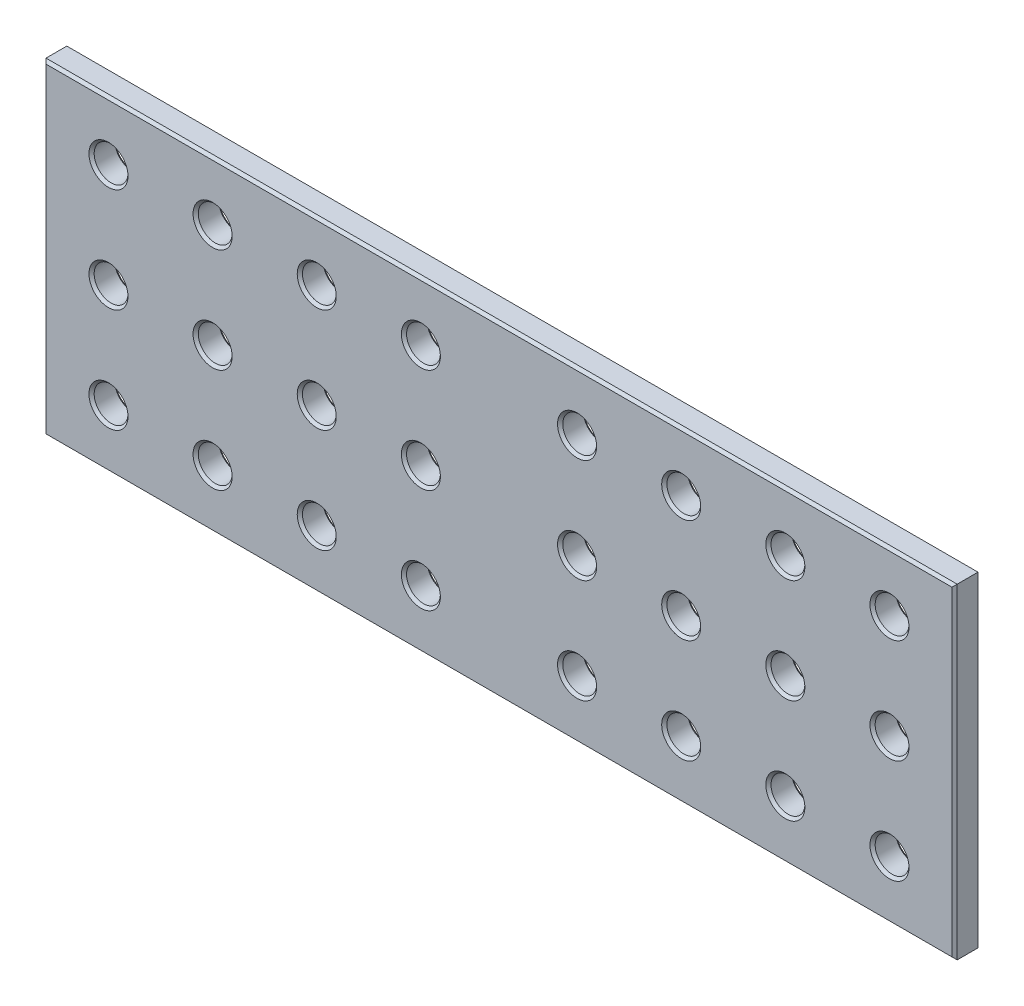
SolidWorks part; units mm, degrees
ref_plane "前视" through (0, 0, 0) normal (0, 0, 1) x (1, 0, 0)
ref_plane "上视" through (0, 0, 0) normal (0, 1, 0) x (1, 0, 0)
ref_plane "右视" through (0, 0, 0) normal (1, 0, 0) x (0, 0, -1)
sketch "草图1" plane through (0, 0, 0) normal (0, 0, 1) x (1, 0, 0)
  line L0 (0, -309.0802) -> (0, 309.0802) construction
  line L1 (-350, -125) -> (350, -125)
  line L2 (-350, -125) -> (-350, 125)
  line L3 (-350, 125) -> (350, 125)
  line L4 (350, -125) -> (350, 125)
  line L5 (-416.575, 0) -> (416.575, 0) construction
  line L6 (-60, 231.9077) -> (-60, -177.8082) construction
  line L7 (-405.3499, 80) -> (106.7949, 80) construction
  line L8 (-300, 281.0174) -> (-300, -177.8082) construction
  line L9 (-140, 189.8136) -> (-140, -190.9976) construction
  line L10 (-220, 297.8551) -> (-220, -190.9976) construction
  circle A0 centre (-300, 80) radius 13
  circle A1 centre (-220, 80) radius 13
  circle A2 centre (-140, 80) radius 13
  circle A3 centre (-60, 80) radius 13
  circle A4 centre (-60, 0) radius 13
  circle A5 centre (-220, 0) radius 13
  circle A6 centre (-300, 0) radius 13
  circle A7 centre (-140, 0) radius 13
  circle A8 centre (-60, -80) radius 13
  circle A9 centre (-140, -80) radius 13
  circle A10 centre (-220, -80) radius 13
  circle A11 centre (-300, -80) radius 13
  circle A12 centre (300, -80) radius 13
  circle A13 centre (220, -80) radius 13
  circle A14 centre (140, -80) radius 13
  circle A15 centre (60, -80) radius 13
  circle A16 centre (140, 0) radius 13
  circle A17 centre (300, 0) radius 13
  circle A18 centre (220, 0) radius 13
  circle A19 centre (60, 0) radius 13
  circle A20 centre (60, 80) radius 13
  circle A21 centre (140, 80) radius 13
  circle A22 centre (220, 80) radius 13
  circle A23 centre (300, 80) radius 13
  dimension "D6" = 26
  dimension "D1" = 700
  dimension "D2" = 250
  dimension "D3" = 80
  dimension "D4" = 50
  dimension "D5" = 80
  dimension "D7" = 80
  dimension "D8" = 80
extrude "基体-拉伸" add sketch "草图1" along normal blind 20
chamfer "倒角1" distance 2 angle 45 56 edges at (287, 80, 0) (127, 80, 0) (47, 0, 0) (287, 0, 0) (73, -80, 0) (233, -80, 0) (-313, -80, 0) (-153, -80, 0) (-127, 0, 0) (-207, 0, 0) (-47, 80, 0) (-207, 80, 0) (0, -125, 0) (350, 0, 0) (0, 125, 0) (-350, 0, 0) (-287, 80, 0) (-127, 80, 0) (-47, 0, 0) (-287, 0, 0) (-73, -80, 0) (-233, -80, 0) (313, -80, 0) (153, -80, 0) (127, 0, 0) (207, 0, 0) (47, 80, 0) (207, 80, 0) (287, 80, 20) (127, 80, 20) (47, 0, 20) (287, 0, 20) (73, -80, 20) (233, -80, 20) (-313, -80, 20) (-153, -80, 20) (-127, 0, 20) (-207, 0, 20) (-47, 80, 20) (-207, 80, 20) (0, 125, 20) (350, 0, 20) (0, -125, 20) (-350, 0, 20) (-287, 80, 20) (-127, 80, 20) (-47, 0, 20) (-287, 0, 20) (-73, -80, 20) (-233, -80, 20) (313, -80, 20) (153, -80, 20) (127, 0, 20) (207, 0, 20) (47, 80, 20) (207, 80, 20)
